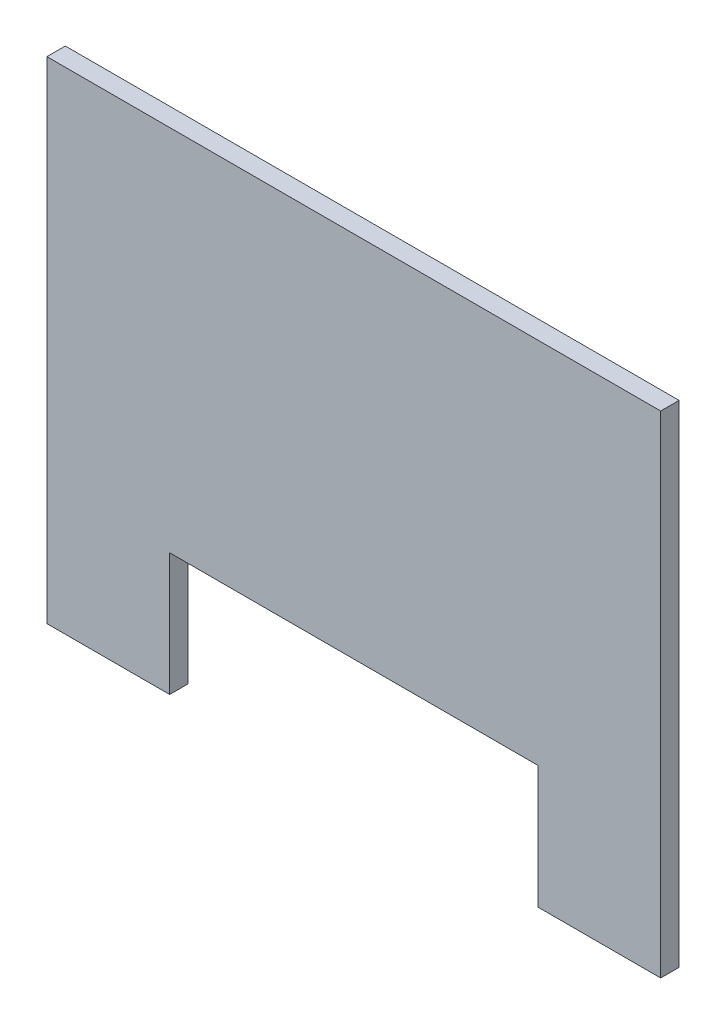
SolidWorks part; units mm, degrees
ref_plane "Plan de face" through (0, 0, 0) normal (0, 0, 1) x (1, 0, 0)
ref_plane "Plan de dessus" through (0, 0, 0) normal (0, 1, 0) x (1, 0, 0)
ref_plane "Plan de droite" through (0, 0, 0) normal (1, 0, 0) x (0, 0, -1)
sketch "Esquisse1" plane through (0, 0, 0) normal (0, 0, 1) x (1, 0, 0)
  line L0 (-16.6015, -41.0721) -> (43.3985, -41.0721)
  line L1 (-36.6015, 18.9279) -> (63.3985, 18.9279)
  line L2 (-36.6015, 18.9279) -> (-36.6015, -21.0018)
  line L4 (63.3985, 18.9279) -> (63.3985, -26.4148)
  line L6 (63.3985, -26.4148) -> (63.3985, -61.0721)
  line L7 (63.3985, -61.0721) -> (43.3985, -61.0721)
  line L8 (43.3985, -41.0721) -> (43.3985, -61.0721)
  line L10 (-36.6015, -21.0018) -> (-36.6015, -61.0721)
  line L11 (-36.6015, -61.0721) -> (-16.6015, -61.0721)
  line L12 (-16.6015, -41.0721) -> (-16.6015, -61.0721)
  dimension "D1" = 100
  dimension "D2" = 80
  dimension "D3" = 60
  dimension "D4" = 80
  dimension "D5" = 20
  dimension "D6" = 20
extrude "Boss.-Extru.1" add sketch "Esquisse1" along normal blind 3
